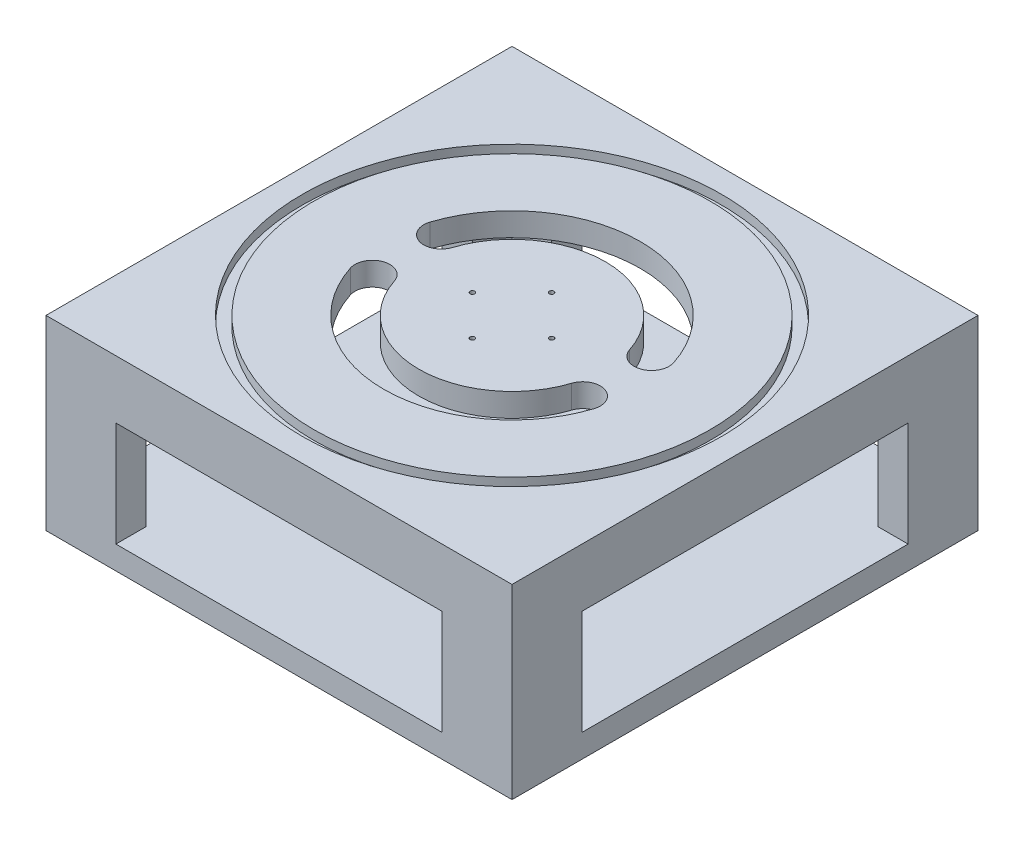
SolidWorks part; units mm, degrees
ref_plane "Alzado" through (0, 0, 0) normal (0, 0, 1) x (1, 0, 0)
ref_plane "Planta" through (0, 0, 0) normal (0, 1, 0) x (1, 0, 0)
ref_plane "Vista lateral" through (0, 0, 0) normal (1, 0, 0) x (0, 0, -1)
sketch "Sketch2" plane through (0, 0, 0) normal (0, 1, 0) x (1, 0, 0)
  line L1 (-100, 100) -> (100, 100)
  line L2 (-100, 100) -> (-100, -100)
  line L3 (-100, -100) -> (100, -100)
  line L4 (100, 100) -> (100, -100)
  dimension "D1" = 200
extrude "Boss-Extrude1" add sketch "Sketch2" along normal blind 10
sketch "Sketch3" plane through (0, 10, 0) normal (0, 1, 0) x (1, 0, 0)
  line L0 (0, 0) -> (55, 0) construction
  arc A20 (-38.018, -12.4352) -> (38.018, -12.4352) centre (0, 0) ccw
  arc A23 (-46.9079, -7.4766) -> (46.9079, -7.4766) centre (0, 0) ccw construction
  arc A26 (-52.2747, -17.0984) -> (52.2747, -17.0984) centre (0, 0) ccw
  arc A30 (38.018, 12.4352) -> (52.2747, 17.0984) centre (45.1463, 14.7668) ccw
  arc A31 (38.018, -12.4352) -> (52.2747, -17.0984) centre (45.1463, -14.7668) cw
  arc A32 (-38.018, -12.4352) -> (-52.2747, -17.0984) centre (-45.1463, -14.7668) ccw
  arc A33 (-38.018, 12.4352) -> (-52.2747, 17.0984) centre (-45.1463, 14.7668) cw
  arc A34 (38.018, 12.4352) -> (-38.018, 12.4352) centre (0, 0) ccw
  arc A35 (46.9079, 7.4766) -> (-46.9079, 7.4766) centre (0, 0) ccw construction
  arc A36 (52.2747, 17.0984) -> (-52.2747, 17.0984) centre (0, 0) ccw
  point P15 (0, 0)
sketch "Sketch4" plane through (0, 0, 0) normal (0, -1, 0) x (1, 0, 0)
  line L2 (-100, -100) -> (-100, 100)
  line L3 (-100, 100) -> (100, 100)
  line L4 (100, -100) -> (100, 100)
  line L5 (-100, -100) -> (0, 0) construction
  line L6 (-100, 100) -> (-145, 145) construction
  line L7 (100, -100) -> (-100, -100)
  line L8 (95.4594, 95.4594) -> (145, 145) construction
  line L9 (-87, 87) -> (87, 87)
  line L10 (-87, 87) -> (-87, -87)
  line L11 (-87, -87) -> (87, -87)
  line L12 (87, 87) -> (87, -87)
  line L14 (-145, -145) -> (0, 0) construction
  line L15 (95.4594, 95.4594) -> (100, 100) construction
  line L16 (-95.4594, 95.4594) -> (145, -145) construction
  line L17 (-95.4594, 95.4594) -> (145, -145) construction
sketch "Sketch12" plane through (0, 10, 0) normal (0, 1, 0) x (1, 0, 0)
  circle A0 centre (0, 0) radius 85
  circle A1 centre (0, 0) radius 90
extrude "Cut-Extrude8" cut sketch "Sketch12" against normal blind 4
sketch "Sketch13" plane through (0, 10, 0) normal (0, 1, 0) x (1, 0, 0)
  circle A0 centre (0, 0) radius 17 construction
  circle A1 centre (0, 17) radius 1
  circle A2 centre (17, 0) radius 1
  circle A3 centre (0, -17) radius 1
  circle A4 centre (-17, 0) radius 1
  point P14 (0, 0)
  dimension "D1" = 4
extrude "Cut-Extrude9" cut sketch "Sketch13" against normal through all
extrude "Boss-Extrude4" add sketch "Sketch4" along normal blind 60
sketch "Sketch14" plane through (0, 0, 100) normal (0, 0, 1) x (1, 0, 0)
  line L1 (100, -60) -> (-100, -60) construction
  line L2 (0, -15) -> (70, -15)
  line L3 (70, -15) -> (70, -60)
  line L4 (70, -60) -> (-70, -60)
  line L5 (-70, -60) -> (-70, -15)
  line L6 (-70, -15) -> (0, -15)
  dimension "D1" = 45
  dimension "D2" = 140
  dimension "D3" = 70
  dimension "D4" = 0
extrude "Cut-Extrude10" cut sketch "Sketch14" against normal through all both and the other way through all contours L6 L2 L3 L4 L5
sketch "Sketch15" plane through (-100, 0, 0) normal (-1, 0, 0) x (0, 0, 1)
  line L0 (0, -60) -> (-70, -60)
  line L1 (100, -60) -> (-100, -60) construction
  line L2 (-70, -60) -> (-70, -15)
  line L3 (-70, -15) -> (70, -15)
  line L4 (70, -15) -> (70, -60)
  line L5 (70, -60) -> (0, -60)
  dimension "D1" = 70
  dimension "D2" = 140
  dimension "D3" = 45
extrude "Cut-Extrude11" cut sketch "Sketch15" against normal through all both and the other way through all contours L3 L4 L5 L0 L2
sketch "Sketch17" plane through (0, 10, 0) normal (0, 1, 0) x (1, 0, 0)
  circle A0 centre (0, 0) radius 5 construction
extrude "Cut-Extrude12" cut sketch "Sketch3" against normal blind 10
sketch "Sketch19" plane through (0, -60, 0) normal (0, -1, 0) x (1, 0, 0)
  line L1 (-100, 100) -> (100, 100)
  line L2 (-100, 100) -> (-100, -100)
  line L3 (-100, -100) -> (100, -100)
  line L4 (100, 100) -> (100, -100)
extrude "Boss-Extrude5" add sketch "Sketch19" along normal blind 10
